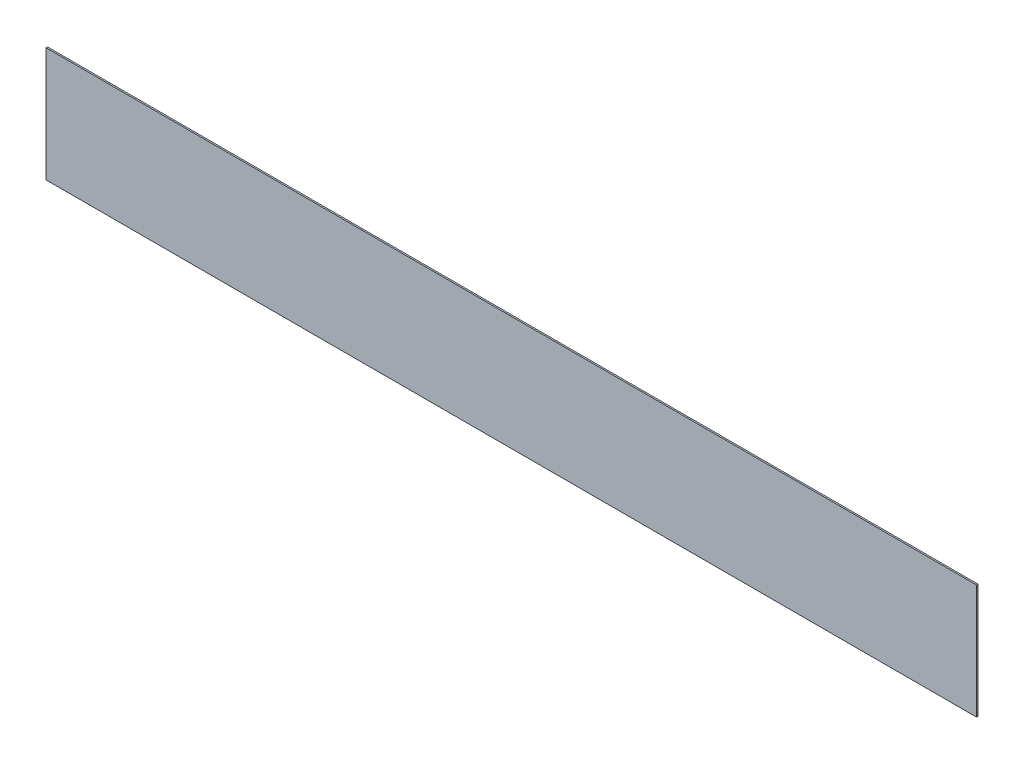
SolidWorks part; units mm, degrees
ref_plane "Front Plane" through (0, 0, 0) normal (0, 0, 1) x (1, 0, 0)
ref_plane "Top Plane" through (0, 0, 0) normal (0, 1, 0) x (1, 0, 0)
ref_plane "Right Plane" through (0, 0, 0) normal (1, 0, 0) x (0, 0, -1)
sketch "Sketch1" plane through (0, 0, 0) normal (0, 0, 1) x (1, 0, 0)
  line L1 (0, 0) -> (813, 0)
  line L2 (0, 0) -> (0, 100)
  line L3 (0, 100) -> (813, 100)
  line L4 (813, 0) -> (813, 100)
  dimension "D1" = 100
  dimension "D2" = 813
extrude "Boss-Extrude1" add sketch "Sketch1" along normal blind 1.27
